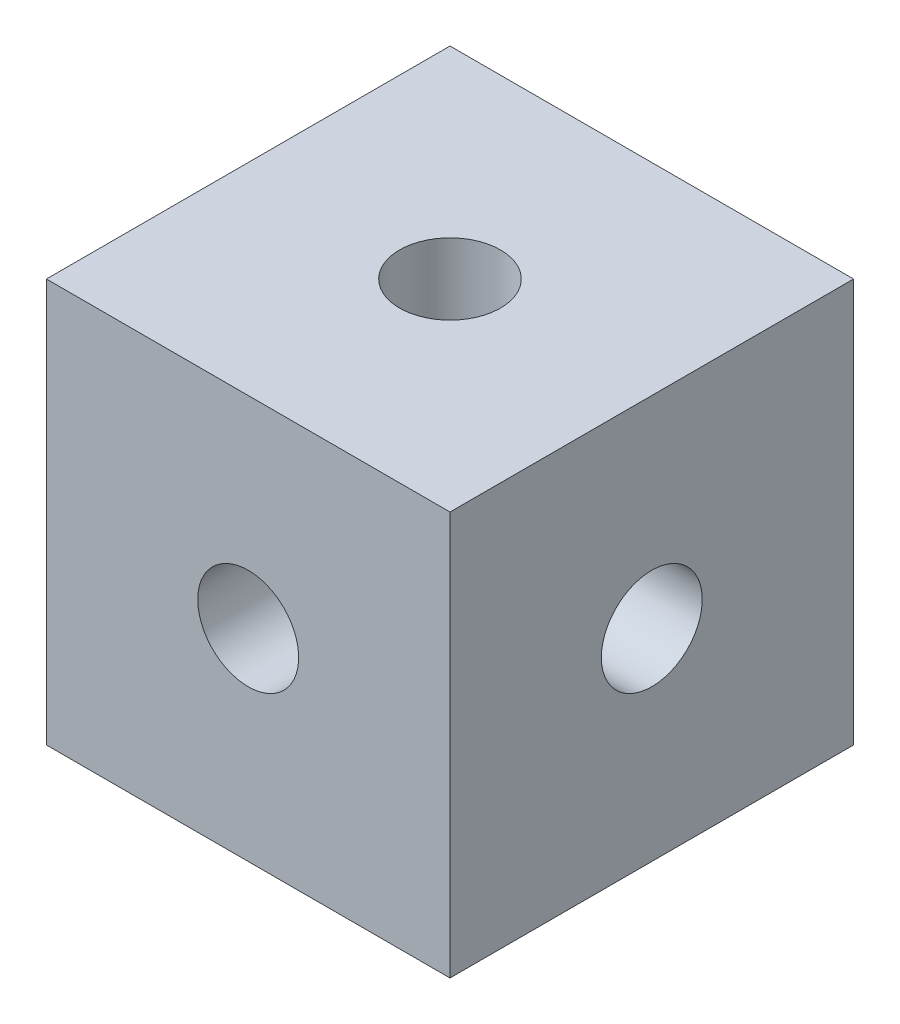
SolidWorks part; units mm, degrees
ref_plane "前视基准面" through (0, 0, 0) normal (0, 0, 1) x (1, 0, 0)
ref_plane "上视基准面" through (0, 0, 0) normal (0, 1, 0) x (1, 0, 0)
ref_plane "右视基准面" through (0, 0, 0) normal (1, 0, 0) x (0, 0, -1)
other "Configuration Table"
sketch "草图1" plane through (0, 0, 0) normal (0, 1, 0) x (1, 0, 0)
  line L1 (-5, -5) -> (5, -5)
  line L2 (-5, -5) -> (-5, 5)
  line L3 (-5, 5) -> (5, 5)
  line L4 (5, -5) -> (5, 5)
  line L5 (-5, -5) -> (5, 5) construction
  line L6 (-5, 5) -> (5, -5) construction
  point P0 (0, 0)
  dimension "D1" = 10
  dimension "D2" = 10
extrude "凸台-拉伸1" add sketch "草图1" along normal blind 10
sketch "草图4" plane through (0, 0, 0) normal (0, -1, 0) x (-1, 0, 0)
  point P0 (0, 0)
hole_wizard "M3 螺纹孔1" positions "草图4" profile "草图3" tap size "M3" standard "ISO" end condition through all
sketch "草图3" plane through (0, 0, 0) normal (1, 0, 0) x (0, 0, -1)
  line L0 (0, 0) -> (0, 10)
  line L1 (0, 10) -> (1.25, 10)
  line L2 (1.25, 10) -> (1.25, 0.275)
  line L3 (1.25, 0.275) -> (1.525, 0)
  line L5 (1.525, 0) -> (0, 0)
  line L6 (-1.25, 0.275) -> (-1.525, 0) construction
  line L11 (0, -6.35) -> (0, 107.95) construction
  dimension "通孔螺纹孔钻头直径" = 2.5
  dimension "通孔螺纹孔钻头深度" = 10
  dimension "近端锥形沉头孔直径" = 3.05
  dimension "近端锥形沉头孔角度" = 90
cosmetic thread "孔螺纹线1"
sketch "草图7" plane through (0, 0, -5) normal (0, 0, -1) x (-1, 0, 0)
  line L0 (-5, 5) -> (5, 5) construction
  line L1 (-5, 10) -> (-5, 0) construction
  line L2 (5, 10) -> (5, 0) construction
  line L4 (0, 10) -> (0, 0) construction
  line L5 (-5, 10) -> (5, 10) construction
  point P18 (0, 5)
hole_wizard "M3 螺纹孔2" positions "草图7" profile "草图6" tap size "M3" standard "ISO" end condition through all
sketch "草图6" plane through (0, 5, -5) normal (1, 0, 0) x (0, 1, 0)
  line L0 (0, 0) -> (0, 10)
  line L1 (0, 10) -> (1.25, 10)
  line L2 (1.25, 10) -> (1.25, 0.275)
  line L3 (1.25, 0.275) -> (1.525, 0)
  line L5 (1.525, 0) -> (0, 0)
  line L6 (-1.25, 0.275) -> (-1.525, 0) construction
  line L11 (0, -6.35) -> (0, 107.95) construction
  dimension "通孔螺纹孔钻头直径" = 2.5
  dimension "通孔螺纹孔钻头深度" = 10
  dimension "近端锥形沉头孔直径" = 3.05
  dimension "近端锥形沉头孔角度" = 90
cosmetic thread "孔螺纹线2"
sketch "草图10" plane through (-5, 0, 0) normal (-1, 0, 0) x (0, 0, 1)
  line L0 (-5, 5) -> (5, 5) construction
  line L1 (-5, 10) -> (-5, 0) construction
  line L2 (5, 10) -> (5, 0) construction
  line L4 (0, 10) -> (0, 0) construction
  line L5 (-5, 10) -> (5, 10) construction
  line L6 (-5, 0) -> (5, 0) construction
  point P17 (0, 5)
hole_wizard "M3 螺纹孔3" positions "草图10" profile "草图9" tap size "M3" standard "ISO" end condition through all
sketch "草图9" plane through (-5, 5, 0) normal (0, 1, 0) x (0, 0, 1)
  line L0 (0, 0) -> (0, 10)
  line L1 (0, 10) -> (1.25, 10)
  line L2 (1.25, 10) -> (1.25, 0.275)
  line L3 (1.25, 0.275) -> (1.525, 0)
  line L5 (1.525, 0) -> (0, 0)
  line L6 (-1.25, 0.275) -> (-1.525, 0) construction
  line L11 (0, -6.35) -> (0, 107.95) construction
  dimension "通孔螺纹孔钻头直径" = 2.5
  dimension "通孔螺纹孔钻头深度" = 10
  dimension "近端锥形沉头孔直径" = 3.05
  dimension "近端锥形沉头孔角度" = 90
cosmetic thread "孔螺纹线3"
